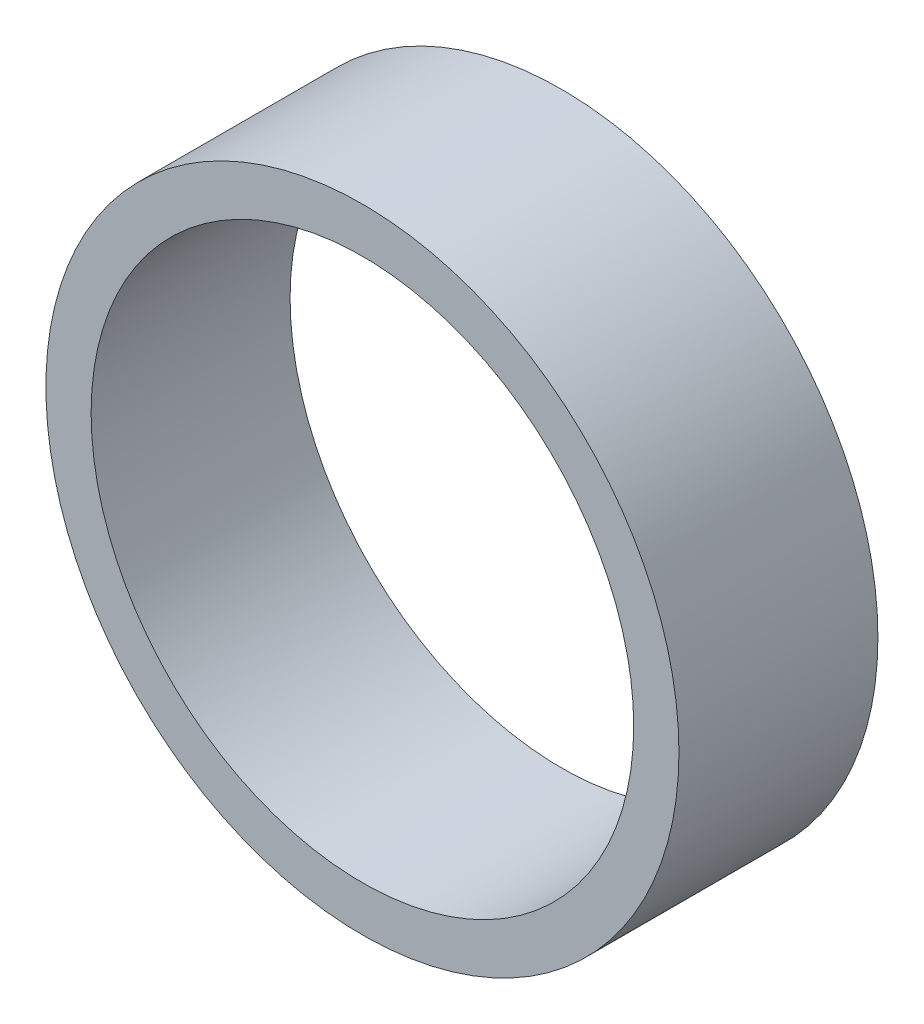
SolidWorks part; units mm, degrees
ref_plane "Front Plane" through (0, 0, 0) normal (0, 0, 1) x (1, 0, 0)
ref_plane "Top Plane" through (0, 0, 0) normal (0, 1, 0) x (1, 0, 0)
ref_plane "Right Plane" through (0, 0, 0) normal (1, 0, 0) x (0, 0, -1)
sketch "Sketch1" plane through (0, 0, 0) normal (0, 0, 1) x (1, 0, 0)
  circle A0 centre (0, 0) radius 3
  circle A1 centre (0, 0) radius 3.5
  dimension "D1" = 6
  dimension "D2" = 7
extrude "Boss-Extrude1" add sketch "Sketch1" against normal blind 2.2
scale "Scale1" scale about origin uniform scaling yes scale factor 1.5
